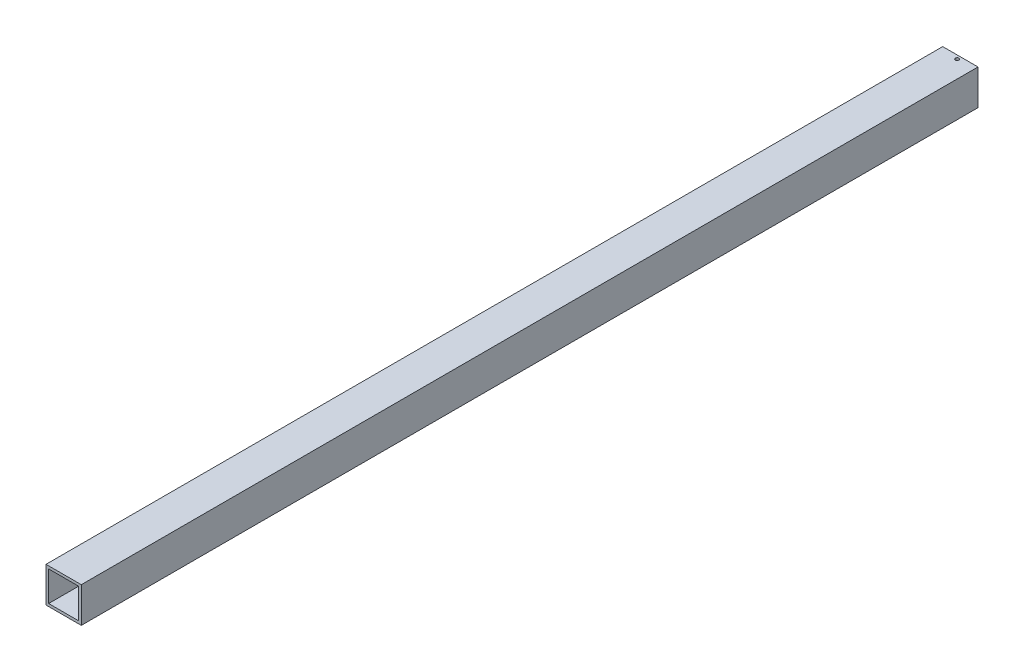
SolidWorks part; units mm, degrees
ref_plane "Płaszczyzna przednia" through (0, 0, 0) normal (0, 0, 1) x (1, 0, 0)
ref_plane "Płaszczyzna górna" through (0, 0, 0) normal (0, 1, 0) x (1, 0, 0)
ref_plane "Płaszczyzna prawa" through (0, 0, 0) normal (1, 0, 0) x (0, 0, -1)
sketch "Szkic1" plane through (0, 0, 0) normal (0, 0, 1) x (1, 0, 0)
  line L2 (-30.423, 18.5) -> (-30.423, -1.5)
  line L3 (-30.423, -1.5) -> (-10.423, -1.5)
  line L4 (-10.423, 18.5) -> (-10.423, -1.5)
  line L8 (-30.423, 18.5) -> (-10.423, 18.5)
  line L10 (-28.923, 17) -> (-11.923, 17)
  line L11 (-28.923, 17) -> (-28.923, 0)
  line L12 (-28.923, 0) -> (-11.923, 0)
  line L13 (-11.923, 17) -> (-11.923, 0)
  dimension "D1" = 20
  dimension "D2" = 20
  dimension "D3" = 1.5
  dimension "D4" = 1.5
  dimension "D5" = 1.5
  dimension "D6" = 1.5
extrude "Dodanie-wyciągnięcie1" add sketch "Szkic1" along normal up to surface (508.3154 mm away)
sketch "Szkic3" plane through (0, 18.5, 0) normal (0, 1, 0) x (1, 0, 0)
  circle A0 centre (-20.1716, -2.0464) radius 1
extrude "Wytnij-wyciągnięcie1" cut sketch "Szkic3" against normal through all
